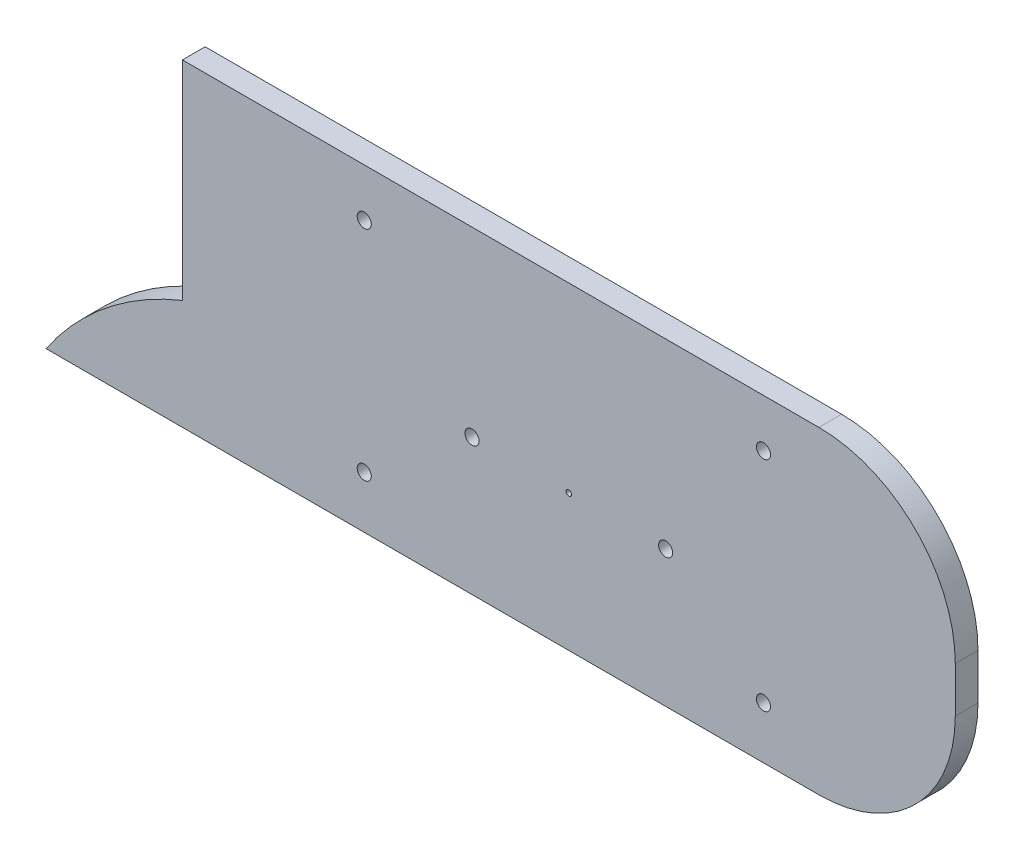
SolidWorks part; units mm, degrees
material "1060 Alloy"
ref_plane "Front Plane" through (0, 0, 0) normal (0, 0, 1) x (1, 0, 0)
ref_plane "Top Plane" through (0, 0, 0) normal (0, 1, 0) x (1, 0, 0)
ref_plane "Right Plane" through (0, 0, 0) normal (1, 0, 0) x (0, 0, -1)
sketch "Sketch2" plane through (0, 0, 0) normal (0, 0, 1) x (1, 0, 0)
  line L0 (0, 0) -> (431.8, 0)
  line L1 (76.2, 0) -> (76.2, 142.4009) construction
  line L2 (152.4, 0) -> (152.4, 186.487) construction
  line L9 (431.8, 177.8) -> (152.4, 177.8)
  line L14 (508, 76.2) -> (508, 101.6)
  line L15 (152.4, 177.8) -> (76.2, 177.8)
  line L16 (76.2, 177.8) -> (76.2, 61.4013)
  arc A5 (0, 0) -> (76.2, 61.4013) centre (138.3869, -93.7571) cw
  arc A6 (431.8, 0) -> (508, 76.2) centre (431.8, 76.2) ccw
  arc A7 (508, 101.6) -> (431.8, 177.8) centre (431.8, 101.6) ccw
  dimension "D6" = 167.1566
  dimension "D7" = 142.4009
  dimension "D5" = 177.8
  dimension "D1" = 76.2
  dimension "D4" = 431.8
  dimension "D9" = 138.3869
  dimension "D2" = 76.2
  dimension "D3" = 152.4
  dimension "D8" = 186.487
extrude "Boss-Extrude1" add sketch "Sketch2" along normal blind 12.7
sketch "Sketch3" plane through (0, 0, 0) normal (0, 0, -1) x (-1, 0, 0)
  line L0 (-76.2, 189.7623) -> (-76.2, -31.0498) construction
  line L1 (-76.2, 29.0821) -> (-501.4435, 29.0821) construction
  line L2 (-431.8, 0) -> (-433.2183, 177.7868) construction
  line L3 (0, 0) -> (-431.8, 0) construction
  arc A0 (-431.8, 177.8) -> (-508, 101.6) centre (-431.8, 101.6) ccw construction
  circle A1 centre (-177.8, 29.0821) radius 3.937
  circle A4 centre (-400.8364, 29.0821) radius 3.937
  circle A7 centre (-400.8364, 151.0021) radius 3.937
  circle A8 centre (-177.8, 151.0021) radius 3.937
  circle A9 centre (-326.4909, 29.0821) radius 3.937 [skipped]
  circle A10 centre (-252.1455, 29.0821) radius 3.937 [skipped]
  circle A11 centre (-326.4909, 151.0021) radius 3.937 [skipped]
  circle A12 centre (-252.1455, 151.0021) radius 3.937 [skipped]
  dimension "D5" = 7.874
  dimension "D10" = 101.6
  dimension "D1" = 76.2
  dimension "D2" = 177.7868
  dimension "D3" = 29.0821
  dimension "D4" = 101.6
  dimension "D8" = 324.6364
  dimension "D9" = 121.92
  dimension "D6" = 4
  dimension "D7" = 2
extrude "Cut-Extrude1" cut sketch "Sketch3" against normal through all
sketch "Sketch4" plane through (0, 0, 12.7) normal (0, 0, 1) x (1, 0, 0)
  line L0 (292.1, 0) -> (292.1, 177.8) construction
  line L1 (0, 0) -> (431.8, 0) construction
  line L2 (431.8, 177.8) -> (76.2, 177.8) construction
  line L3 (76.2, 76.2) -> (508, 76.2) construction
  line L5 (76.2, 177.8) -> (76.2, 61.4013) construction
  circle A0 centre (292.1, 76.2) radius 1.524
  circle A1 centre (237.998, 76.2) radius 3.937
  circle A2 centre (346.202, 76.2) radius 3.937
  dimension "D1" = 3.048
  dimension "D4" = 7.874
  dimension "D5" = 7.874
  dimension "D6" = 54.102
  dimension "D7" = 54.102
  dimension "D2" = 292.1
  dimension "D3" = 76.2
extrude "Cut-Extrude2" cut sketch "Sketch4" against normal through all
equation "\"0.5n\"=0.25"
equation "\".5n\"=0.25"
